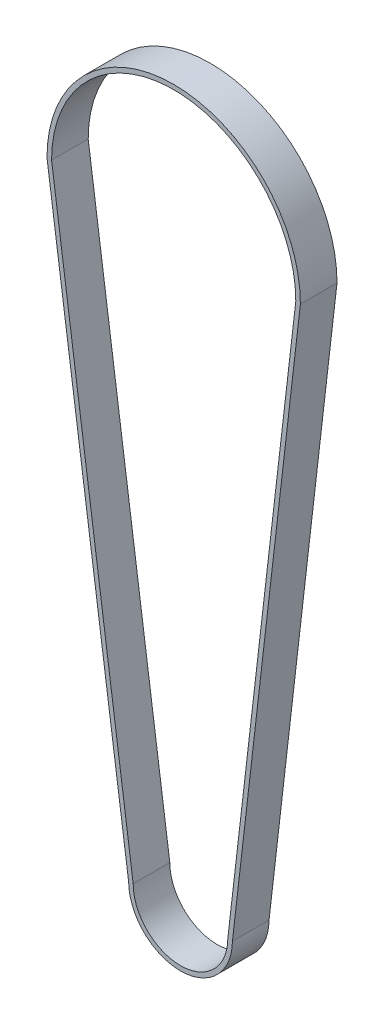
SolidWorks part; units mm, degrees
ref_plane "Front Plane" through (0, 0, 0) normal (0, 0, 1) x (1, 0, 0)
ref_plane "Top Plane" through (0, 0, 0) normal (0, 1, 0) x (1, 0, 0)
ref_plane "Right Plane" through (0, 0, 0) normal (1, 0, 0) x (0, 0, -1)
sketch "Sketch2" plane through (0, 0, 0) normal (0, 0, 1) x (1, 0, 0)
  line L0 (-22.9662, 46.7523) -> (-9.5998, -49.1912)
  line L1 (17.0338, 46.7523) -> (5.9002, -49.1912)
  line L2 (-23.7161, 46.6999) -> (-10.3497, -49.2444)
  line L3 (17.7838, 46.7086) -> (6.6501, -49.2355)
  arc A0 (-22.9662, 46.7523) -> (17.0338, 46.7523) centre (-2.9662, 46.7523) cw
  arc A1 (-9.5998, -49.1912) -> (5.9002, -49.1912) centre (-1.8498, -49.1912) ccw
  arc A2 (-10.3497, -49.2444) -> (6.6501, -49.2355) centre (-1.8498, -49.1912) ccw
  arc A3 (-23.7161, 46.6999) -> (17.7838, 46.7086) centre (-2.9662, 46.7523) cw
  dimension "D1" = 0.75
extrude "Boss-Extrude1" add sketch "Sketch2" along normal blind 6
